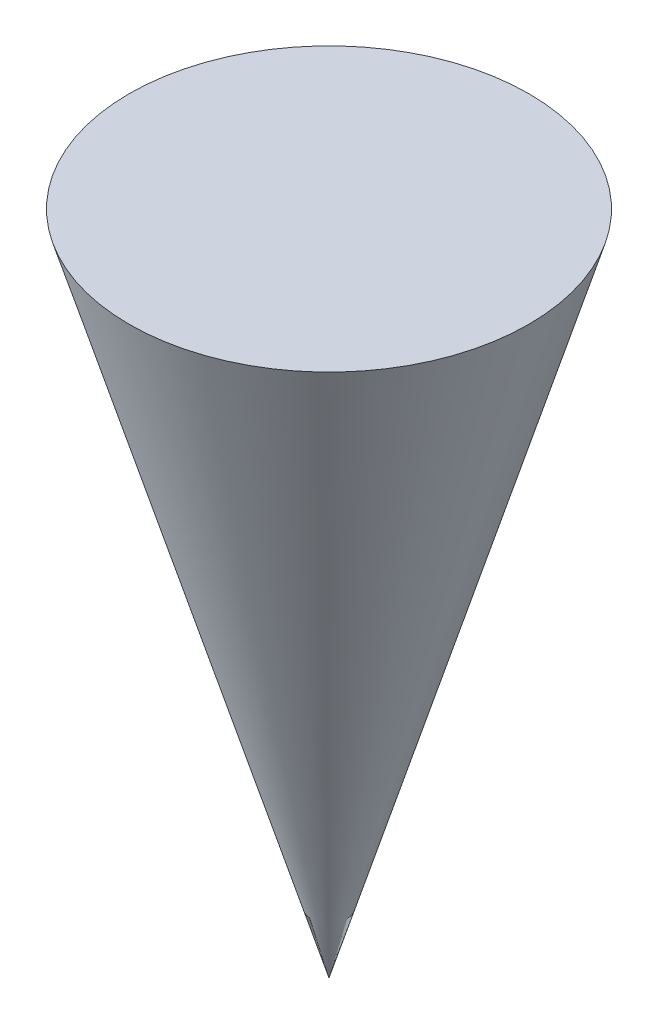
SolidWorks part; units mm, degrees
ref_plane "Front Plane" through (0, 0, 0) normal (0, 0, 1) x (1, 0, 0)
ref_plane "Top Plane" through (0, 0, 0) normal (0, 1, 0) x (1, 0, 0)
ref_plane "Right Plane" through (0, 0, 0) normal (1, 0, 0) x (0, 0, -1)
sketch "Sketch2" plane through (0, 0, 0) normal (0, 0, 1) x (1, 0, 0)
  line L0 (0, 0) -> (30, 0)
  line L1 (30, 0) -> (0, -100)
  line L2 (0, -100) -> (0, 0) construction
  line L3 (0, 0) -> (0, -100)
revolve "Revolve1" add sketch "Sketch2" angle 360 about L2
